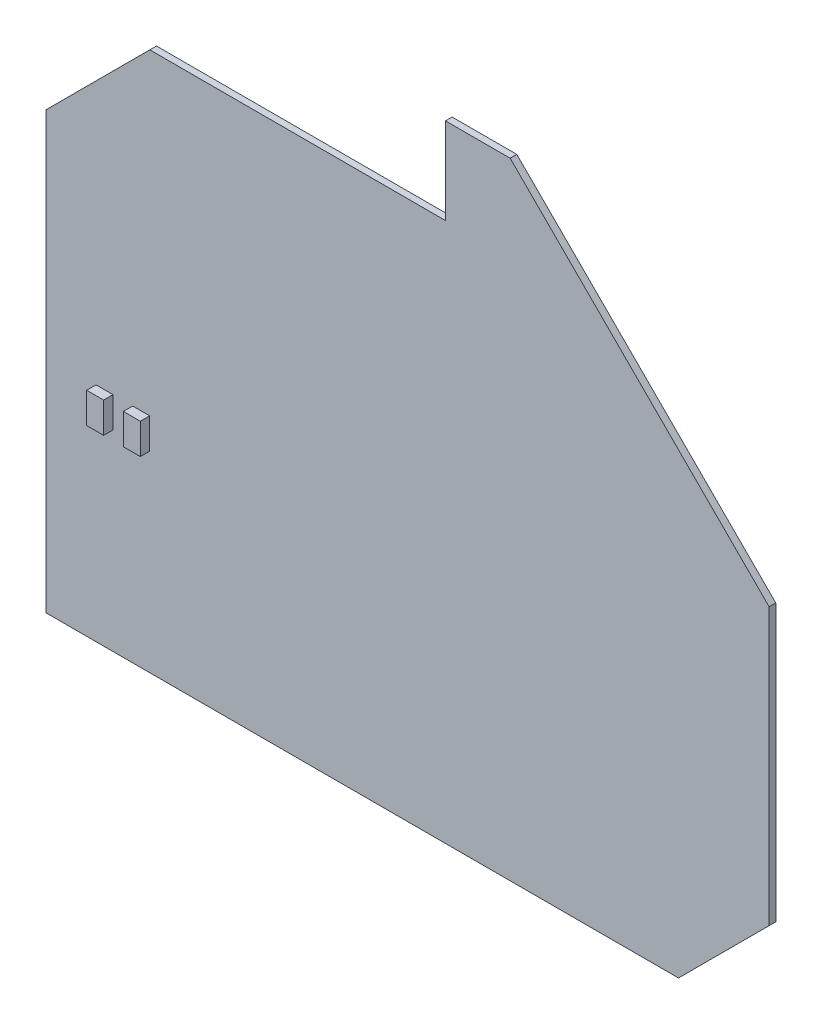
SolidWorks part; units mm, degrees
ref_plane "Спереди" through (0, 0, 0) normal (0, 0, 1) x (1, 0, 0)
ref_plane "Сверху" through (0, 0, 0) normal (0, 1, 0) x (1, 0, 0)
ref_plane "Справа" through (0, 0, 0) normal (1, 0, 0) x (0, 0, -1)
sketch "Эскиз1" plane through (0, 0, 0) normal (0, 0, 1) x (1, 0, 0)
  line L0 (55.245, 7.62) -> (55.245, 33.274)
  line L1 (55.245, 33.274) -> (61.341, 39.37)
  line L2 (61.341, 39.37) -> (78.74, 39.37)
  line L3 (78.74, 39.37) -> (78.74, 44.45)
  line L4 (78.74, 44.45) -> (82.55, 44.45)
  line L5 (82.55, 44.45) -> (97.79, 29.21)
  line L6 (97.79, 29.21) -> (97.79, 12.954)
  line L7 (97.79, 12.954) -> (92.456, 7.62)
  line L8 (92.456, 7.62) -> (55.245, 7.62)
extrude "BOARD" add sketch "Эскиз1" along normal blind 0.3912 separate body
ref_plane "Плоскость4" through (0, 0, 0.3912) normal (0, 0, 1) x (1, 0, 0)
sketch "Эскиз2" plane through (0, 0, 0.3912) normal (0, 0, 1) x (1, 0, 0)
  line L0 (61.333, 20.412) -> (61.333, 19.212)
  line L1 (61.333, 19.212) -> (61.333, 18.912)
  line L2 (61.333, 18.912) -> (60.333, 18.912)
  line L3 (60.333, 18.912) -> (60.333, 19.212)
  line L4 (60.333, 19.212) -> (60.333, 20.412)
  line L5 (60.333, 20.412) -> (60.333, 20.712)
  line L6 (60.333, 20.712) -> (61.333, 20.712)
  line L7 (61.333, 20.712) -> (61.333, 20.412)
extrude "RESC1608X55X30ML20T10-1" add sketch "Эскиз2" along normal blind 0.55 separate body
sketch "Эскиз3" plane through (0, 0, 0.3912) normal (0, 0, 1) x (1, 0, 0)
  line L0 (59.174, 20.412) -> (59.174, 19.212)
  line L1 (59.174, 19.212) -> (59.174, 18.912)
  line L2 (59.174, 18.912) -> (58.174, 18.912)
  line L3 (58.174, 18.912) -> (58.174, 19.212)
  line L4 (58.174, 19.212) -> (58.174, 20.412)
  line L5 (58.174, 20.412) -> (58.174, 20.712)
  line L6 (58.174, 20.712) -> (59.174, 20.712)
  line L7 (59.174, 20.712) -> (59.174, 20.412)
extrude "RESC1608X55X30ML20T10-2" add sketch "Эскиз3" along normal blind 0.55 separate body
sketch "CSR8645-1 [0]" plane through (0, 0, 0.3912) normal (0, 0, 1) x (1, 0, 0)
  line L0 (88.6686, 15.2654) -> (88.6686, 30.5926)
  line L1 (88.6686, 30.5926) -> (62.7415, 30.5926)
  line L2 (62.7415, 30.5926) -> (62.7415, 15.2654)
  line L3 (62.7415, 15.2654) -> (88.6686, 15.2654)
sketch "via-1 [0]" plane through (0, 0, 0.3912) normal (0, 0, 1) x (1, 0, 0)
  line L0 (56.6422, 22.7331) -> (60.5536, 22.7331)
  line L1 (60.5536, 22.7331) -> (60.5536, 24.9936)
  line L2 (60.5536, 24.9936) -> (56.6422, 24.9936)
  line L3 (56.6422, 24.9936) -> (56.6422, 22.7331)
sketch "DIP3-1 [0]" plane through (0, 0, 0.3912) normal (0, 0, 1) x (1, 0, 0)
  line L0 (61.74, 25.654) -> (61.74, 35.9408)
  line L1 (61.74, 35.9408) -> (56.896, 35.9408)
  line L2 (56.896, 35.9408) -> (56.896, 25.654)
  line L3 (56.896, 25.654) -> (61.74, 25.654)
sketch "Pin Header P=2mm-1 [0]" plane through (0, 0, 0.3912) normal (0, 0, 1) x (1, 0, 0)
  line L0 (57.023, 9.0805) -> (61.5315, 9.0805)
  line L1 (61.5315, 9.0805) -> (61.5315, 13.5888)
  line L2 (61.5315, 13.5888) -> (57.023, 13.5888)
  line L3 (57.023, 13.5888) -> (57.023, 9.0805)
sketch "dip18 header-1 [0]" plane through (0, 0, 0.3912) normal (0, 0, 1) x (1, 0, 0)
  line L0 (87.9366, 38.3538) -> (61.5106, 38.3538)
  line L1 (61.5106, 38.3538) -> (61.5106, 31.9514)
  line L2 (61.5106, 31.9514) -> (87.9366, 31.9514)
  line L3 (87.9366, 31.9514) -> (87.9366, 38.3538)
sketch "dip10 header-1 [0]" plane through (0, 0, 0.3912) normal (0, 0, 1) x (1, 0, 0)
  line L0 (96.8375, 15.9494) -> (96.8375, 32.194)
  line L1 (96.8375, 32.194) -> (90.8685, 32.194)
  line L2 (90.8685, 32.194) -> (90.8685, 15.9494)
  line L3 (90.8685, 15.9494) -> (96.8375, 15.9494)
sketch "dip18 header-2 [0]" plane through (0, 0, 0.3912) normal (0, 0, 1) x (1, 0, 0)
  line L0 (63.3204, 8.0012) -> (89.7464, 8.0012)
  line L1 (89.7464, 8.0012) -> (89.7464, 14.4036)
  line L2 (89.7464, 14.4036) -> (63.3204, 14.4036)
  line L3 (63.3204, 14.4036) -> (63.3204, 8.0012)
